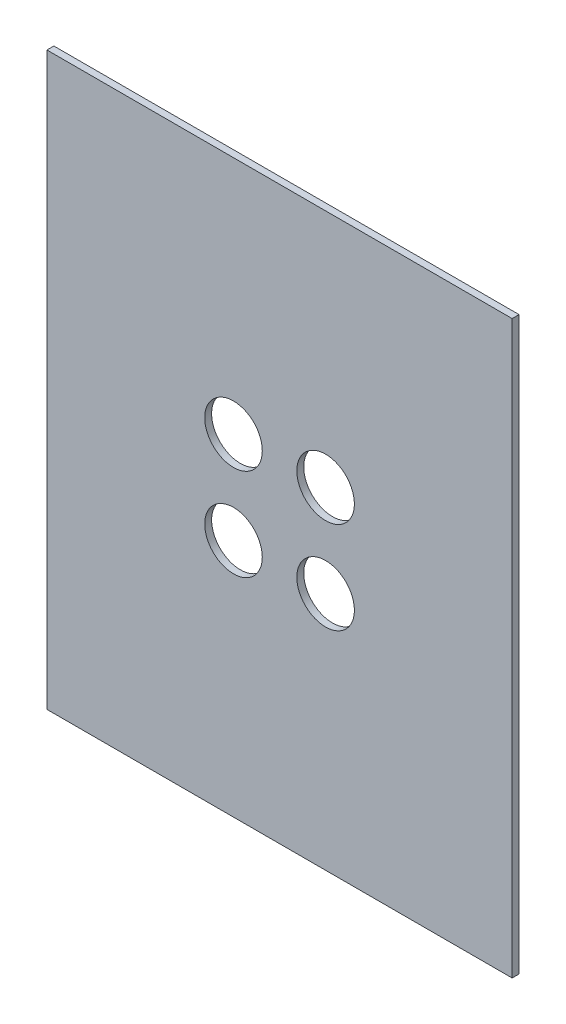
SolidWorks part; units mm, degrees
ref_plane "Plan de face" through (0, 0, 0) normal (0, 0, 1) x (1, 0, 0)
ref_plane "Plan de dessus" through (0, 0, 0) normal (0, 1, 0) x (1, 0, 0)
ref_plane "Plan de droite" through (0, 0, 0) normal (1, 0, 0) x (0, 0, -1)
sketch "Esquisse1" plane through (0, 0, 0) normal (0, 0, 1) x (1, 0, 0)
  line L1 (-63.5626, 77.1925) -> (138.4374, 77.1925)
  line L2 (-63.5626, 77.1925) -> (-63.5626, -170.8075)
  line L3 (-63.5626, -170.8075) -> (138.4374, -170.8075)
  line L4 (138.4374, 77.1925) -> (138.4374, -170.8075)
  dimension "D1" = 202
  dimension "D2" = 248
extrude "Boss.-Extru.1" add sketch "Esquisse1" along normal blind 3
sketch "Esquisse2" plane through (0, 0, 3) normal (0, 0, 1) x (1, 0, 0)
  line L0 (37.4374, 77.1925) -> (37.4374, -170.8075) construction
  line L1 (138.4374, 77.1925) -> (-63.5626, 77.1925) construction
  line L2 (-63.5626, -170.8075) -> (138.4374, -170.8075) construction
  line L3 (-63.5626, -46.8075) -> (138.4374, -46.8075) construction
  line L4 (-63.5626, 77.1925) -> (-63.5626, -170.8075) construction
  line L5 (138.4374, -170.8075) -> (138.4374, 77.1925) construction
  line L6 (57.4374, 77.1925) -> (57.4374, -170.8075) construction
  line L7 (17.4374, 77.1925) -> (17.4374, -170.8075) construction
  line L8 (-63.5626, -26.8075) -> (138.4374, -26.8075) construction
  line L9 (-63.5626, -66.8075) -> (138.4374, -66.8075) construction
  circle A0 centre (17.4374, -26.8075) radius 12.5
  circle A1 centre (57.4374, -26.8075) radius 12.5
  circle A2 centre (57.4374, -66.8075) radius 12.5
  circle A3 centre (17.4374, -66.8075) radius 12.5
  dimension "D5" = 25
  dimension "D6" = 25
  dimension "D7" = 25
  dimension "D8" = 25
  dimension "D1" = 20
  dimension "D2" = 20
  dimension "D3" = 20
  dimension "D4" = 20
extrude "Enlèv. mat.-Extru.1" cut sketch "Esquisse2" against normal blind 3
